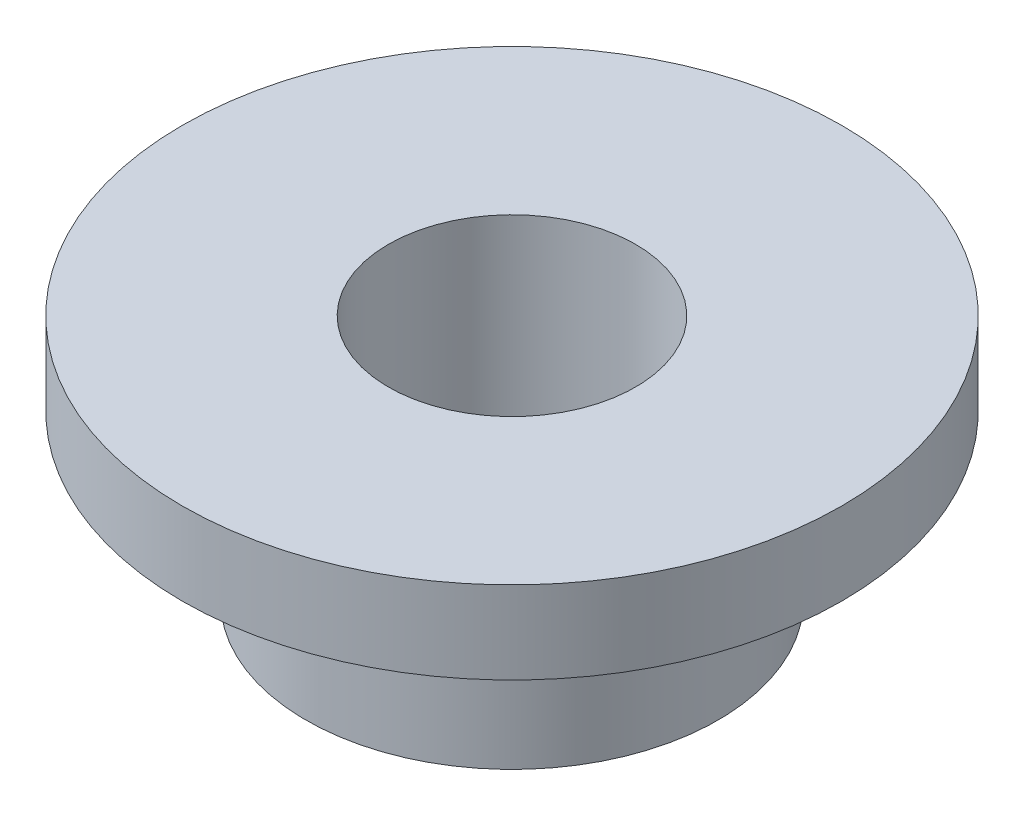
SolidWorks part; units mm, degrees
material "ABS"
ref_plane "Front Plane" through (0, 0, 0) normal (0, 0, 1) x (1, 0, 0)
ref_plane "Top Plane" through (0, 0, 0) normal (0, 1, 0) x (1, 0, 0)
ref_plane "Right Plane" through (0, 0, 0) normal (1, 0, 0) x (0, 0, -1)
sketch "Sketch1" plane through (0, 0, 0) normal (0, 0, 1) x (1, 0, 0)
  line L0 (0, 0) -> (0, -6.6598) construction
  line L2 (-2.5, 0) -> (-1.5, 0)
  line L3 (-2.5, 0) -> (-2.5, 2)
  line L4 (-2.5, 2) -> (-1.5, 2)
  line L5 (-1.5, 0) -> (-1.5, 2)
  line L6 (-1.5, 2) -> (-4, 2)
  line L7 (-1.5, 2) -> (-1.5, 3)
  line L8 (-1.5, 3) -> (-4, 3)
  line L9 (-4, 2) -> (-4, 3)
  dimension "D1" = 3
  dimension "D2" = 5
  dimension "D3" = 8
  dimension "D4" = 2
  dimension "D5" = 1
revolve "Revolve1" add sketch "Sketch1" angle 360 about L0
